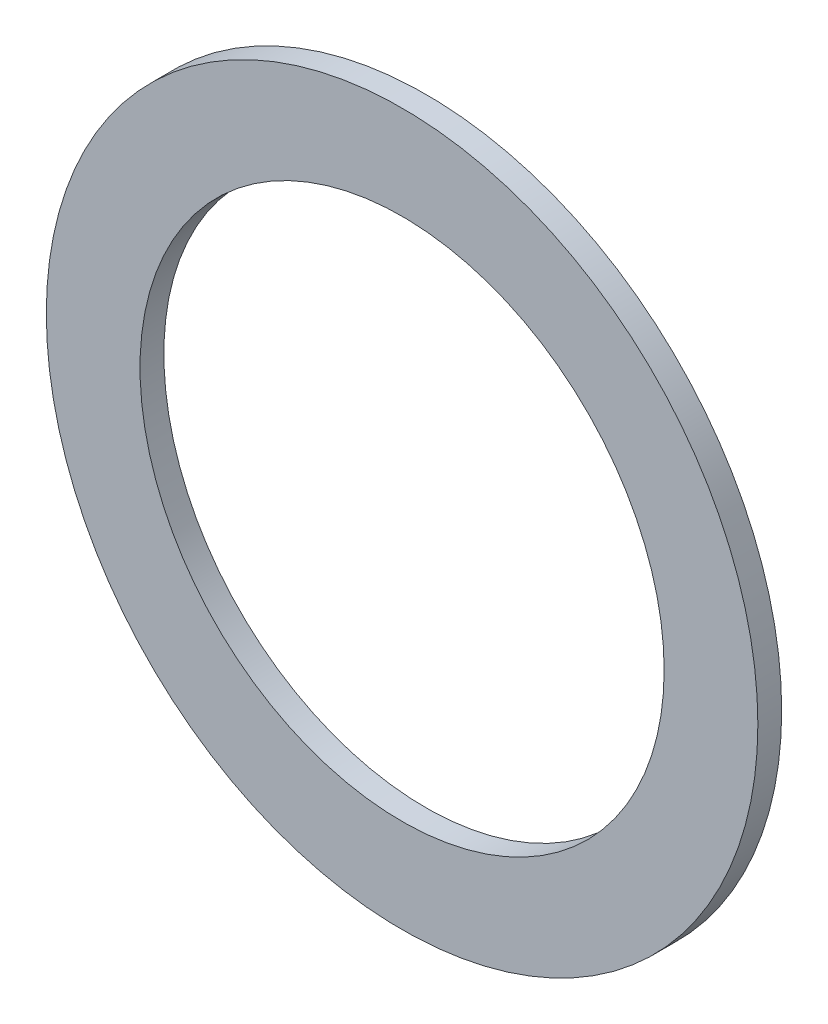
SolidWorks part; units mm, degrees
ref_plane "Plan de face" through (0, 0, 0) normal (0, 0, 1) x (1, 0, 0)
ref_plane "Plan de dessus" through (0, 0, 0) normal (0, 1, 0) x (1, 0, 0)
ref_plane "Plan de droite" through (0, 0, 0) normal (1, 0, 0) x (0, 0, -1)
sketch "Esquisse1" plane through (0, 0, 0) normal (0, 0, 1) x (1, 0, 0)
  line L0 (0, 0) -> (-44.8, 0) construction
  line L1 (0, 44.8) -> (0, -44.8) construction
  circle A0 centre (0, 0) radius 44.8
  circle A5 centre (0, 0) radius 33
  dimension "D1" = 89.6
  dimension "D6" = 66
extrude "Boss.-Extru.1" add sketch "Esquisse1" along normal blind 3
